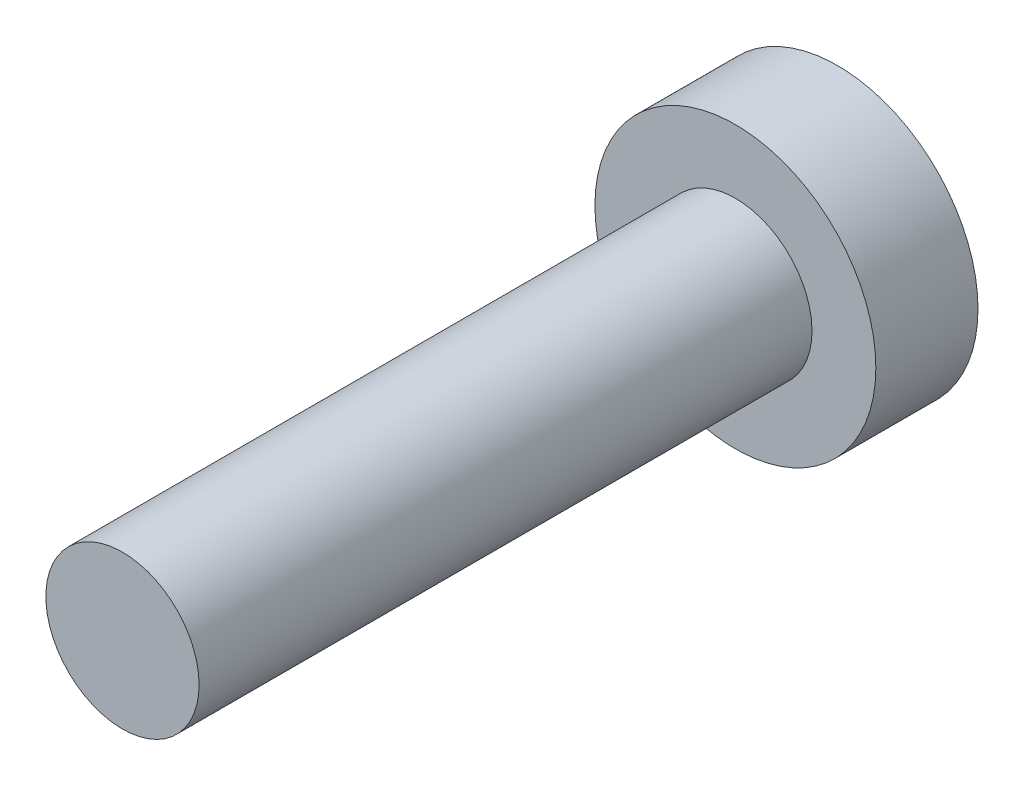
SolidWorks part; units mm, degrees
material "AISI 4340 Steel, normalized"
ref_plane "Front Plane" through (0, 0, 0) normal (0, 0, 1) x (1, 0, 0)
ref_plane "Top Plane" through (0, 0, 0) normal (0, 1, 0) x (1, 0, 0)
ref_plane "Right Plane" through (0, 0, 0) normal (1, 0, 0) x (0, 0, -1)
sketch "Sketch1" plane through (0, 0, 0) normal (0, 0, 1) x (1, 0, 0)
  circle A0 centre (0, 0) radius 2.75
extrude "Head_Envelope" add sketch "Sketch1" along normal blind 2 from offset 2
sketch "Sketch2" plane through (0, 0, 0) normal (0, 0, 1) x (1, 0, 0)
  circle A0 centre (0, 0) radius 1.5
extrude "Thread_Major_Envelope" add sketch "Sketch2" along normal blind 12
